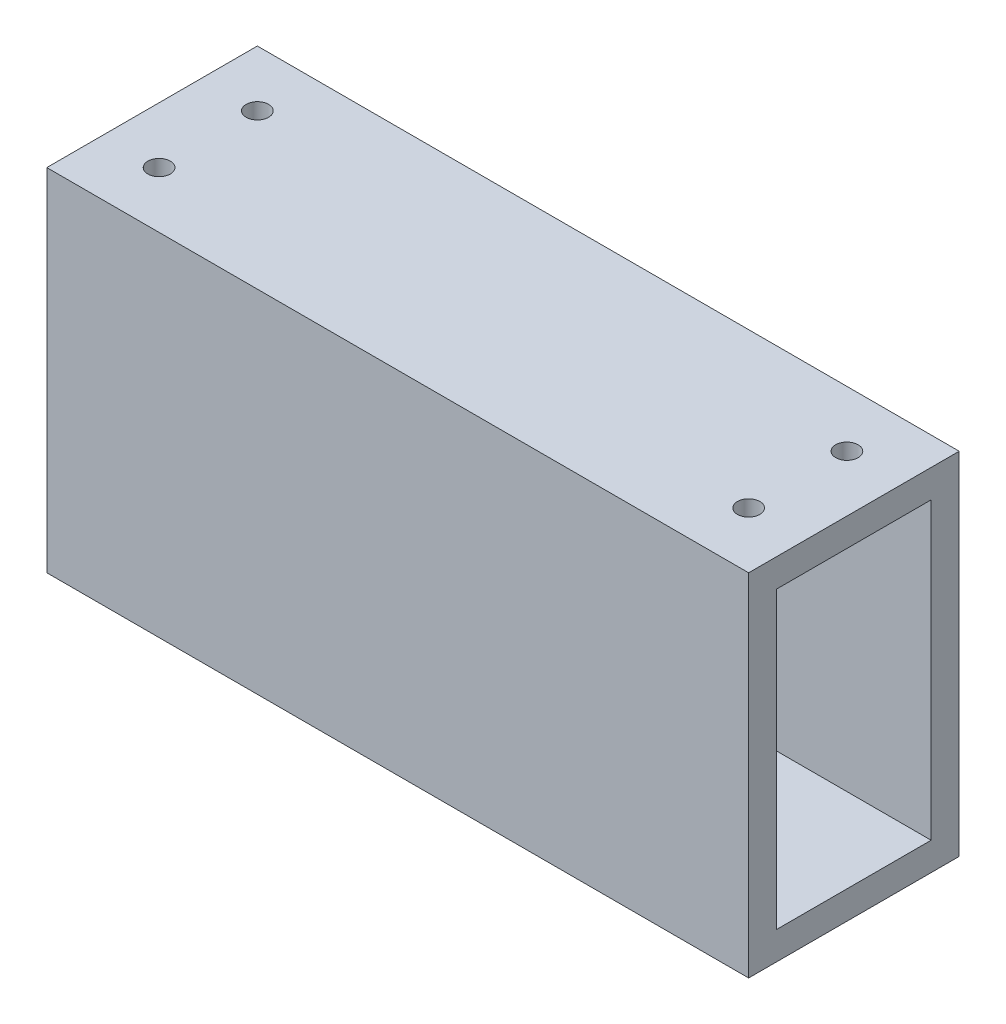
SolidWorks part; units mm, degrees
ref_plane "前视基准面" through (0, 0, 0) normal (0, 0, 1) x (1, 0, 0)
ref_plane "上视基准面" through (0, 0, 0) normal (0, 1, 0) x (1, 0, 0)
ref_plane "右视基准面" through (0, 0, 0) normal (1, 0, 0) x (0, 0, -1)
sketch "草图1" plane through (0, 0, 0) normal (0, 1, 0) x (1, 0, 0)
  line L1 (-50, 15) -> (50, 15)
  line L2 (-50, 15) -> (-50, -15)
  line L3 (-50, -15) -> (50, -15)
  line L4 (50, 15) -> (50, -15)
  line L5 (-50, 15) -> (50, -15) construction
  line L6 (-50, -15) -> (50, 15) construction
  point P0 (0, 0)
  dimension "D1" = 100
  dimension "D2" = 30
extrude "凸台-拉伸1" add sketch "草图1" along normal blind 50
sketch "草图2" plane through (-50, 0, 0) normal (-1, 0, 0) x (0, 0, 1)
  line L0 (-11, 4) -> (11, 4)
  line L1 (11, 4) -> (11, 46)
  line L2 (11, 46) -> (-11, 46)
  line L3 (-11, 46) -> (-11, 4)
  line L4 (-15, 0) -> (15, 0)
  line L5 (15, 0) -> (15, 50)
  line L6 (15, 50) -> (-15, 50)
  line L7 (-15, 50) -> (-15, 0)
  line L8 (-15, 0) -> (15, 0) construction
  line L9 (15, 0) -> (15, 50) construction
  line L10 (15, 50) -> (-15, 50) construction
  line L11 (-15, 50) -> (-15, 0) construction
  dimension "D1" = 0
  dimension "D2" = 4
extrude "切除-拉伸1" cut sketch "草图2" against normal through all
sketch "草图3" plane through (0, 0, 0) normal (0, -1, 0) x (1, 0, 0)
  line L0 (-50, 15) -> (50, 15) construction
  line L1 (50, 15) -> (50, -15) construction
  line L2 (0, 24.6553) -> (0, -28.8009) construction
  circle A0 centre (13, 8) radius 2.1
  circle A1 centre (-13, 8) radius 2.1
  dimension "D1" = 7
  dimension "D2" = 37
extrude "切除-拉伸3" cut sketch "草图3" against normal blind 20
sketch "草图4" plane through (0, 50, 0) normal (0, 1, 0) x (1, 0, 0)
  line L0 (-50, 15) -> (-50, -15) construction
  line L1 (-42, 7) -> (42, 7) construction
  line L2 (-42, 7) -> (-42, -7) construction
  line L3 (-42, -7) -> (42, -7) construction
  line L4 (42, 7) -> (42, -7) construction
  line L5 (-42, 7) -> (42, -7) construction
  line L6 (-42, -7) -> (42, 7) construction
  line L7 (-50, -15) -> (50, -15) construction
  circle A0 centre (-42, 7) radius 1.6
  circle A1 centre (-42, -7) radius 1.6
  circle A2 centre (42, 7) radius 1.6
  circle A3 centre (42, -7) radius 1.6
  point P0 (0, 0)
  dimension "D1" = 8
  dimension "D2" = 8
extrude "切除-拉伸4" cut sketch "草图4" against normal blind 20
